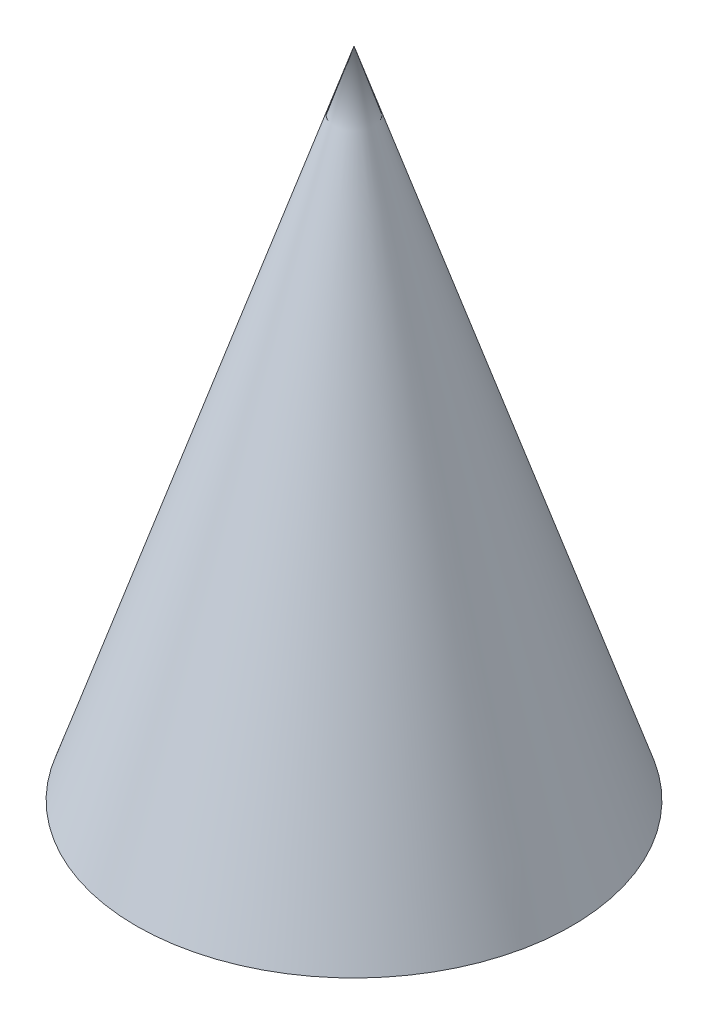
SolidWorks part; units mm, degrees
ref_plane "前视基准面" through (0, 0, 0) normal (0, 0, 1) x (1, 0, 0)
ref_plane "上视基准面" through (0, 0, 0) normal (0, 1, 0) x (1, 0, 0)
ref_plane "右视基准面" through (0, 0, 0) normal (1, 0, 0) x (0, 0, -1)
other "Configuration Table"
sketch "草图1" plane through (0, 0, 0) normal (0, 1, 0) x (1, 0, 0)
  circle A0 centre (0, 0) radius 10
  dimension "D1" = 20
ref_plane "基准面1" through (0, 30, 0) normal (0, 1, 0) x (1, 0, 0)
sketch "草图2" plane through (0, 30, 0) normal (0, 1, 0) x (1, 0, 0)
  point P0 (0, 0)
loft "放样1" add profiles "草图2", "草图1"
